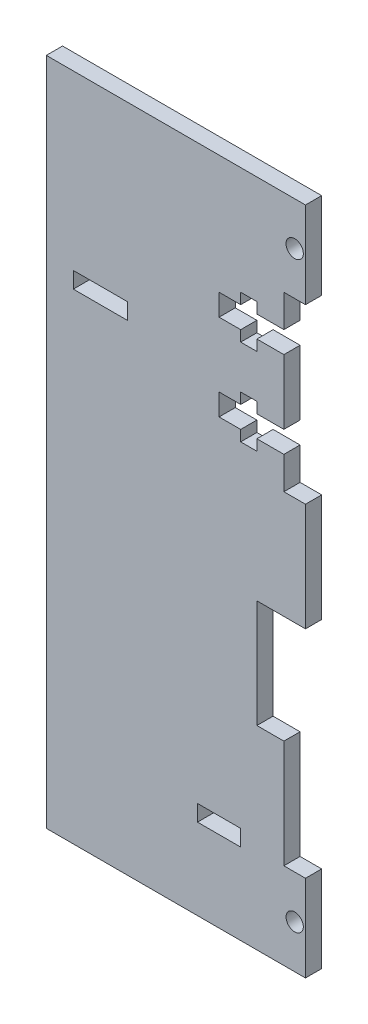
SolidWorks part; units mm, degrees
ref_plane "前视" through (0, 0, 0) normal (0, 0, 1) x (1, 0, 0)
ref_plane "上视" through (0, 0, 0) normal (0, 1, 0) x (1, 0, 0)
ref_plane "右视" through (0, 0, 0) normal (1, 0, 0) x (0, 0, -1)
sketch "草图1" plane through (0, 0, 0) normal (0, 0, 1) x (1, 0, 0)
  line L0 (0, 146) -> (0, 140)
  line L1 (4, 38) -> (4, 54)
  line L2 (-44, 38) -> (-44, 162)
  line L3 (-44, 162) -> (0, 162)
  line L4 (0, 162) -> (4, 162)
  line L5 (4, 162) -> (4, 146)
  line L6 (4, 146) -> (0, 146)
  line L7 (4, 38) -> (-44, 38)
  line L8 (4, 54) -> (0, 54)
  line L10 (0, 54) -> (0, 74)
  line L11 (4, 114) -> (4, 94)
  line L12 (-27.8711, 84) -> (21.6643, 84) construction
  line L14 (-32, 130) -> (-39, 130)
  line L16 (15.9655, 138) -> (-24.4172, 138) construction
  line L17 (-5, 94) -> (-5, 74)
  line L18 (-12, 136) -> (-12, 140)
  line L19 (-12, 140) -> (-8, 140)
  line L20 (-8, 140) -> (-8, 142)
  line L21 (-8, 142) -> (-5, 142)
  line L22 (-5, 142) -> (-5, 140)
  line L23 (-5, 140) -> (0, 140)
  line L24 (-16.0405, 114) -> (46.0459, 114) construction
  line L25 (-34.8085, 54) -> (60.6695, 54) construction
  line L30 (-5, 136) -> (0, 136)
  line L31 (-5, 134) -> (-5, 136)
  line L32 (-8, 134) -> (-5, 134)
  line L33 (-8, 136) -> (-8, 134)
  line L34 (-12, 136) -> (-8, 136)
  line L41 (0, 136) -> (0, 124)
  line L44 (-39, 130) -> (-39, 127)
  line L45 (15.9655, 122) -> (-24.4172, 122) construction
  line L46 (-39, 127) -> (-29, 127)
  line L47 (-16, 56) -> (-8, 56)
  line L48 (-16, 56) -> (-16, 53)
  line L49 (-16, 53) -> (-8, 53)
  line L50 (-12, 124) -> (-8, 124)
  line L51 (-8, 124) -> (-8, 126)
  line L52 (-8, 56) -> (-8, 53)
  line L57 (4, 94) -> (-5, 94)
  line L62 (-8, 126) -> (-5, 126)
  line L63 (-5, 126) -> (-5, 124)
  line L64 (-5, 124) -> (0, 124)
  line L65 (-5, 120) -> (0, 120)
  line L66 (-5, 118) -> (-5, 120)
  line L67 (-5, 74) -> (0, 74)
  line L69 (-29, 130) -> (-32, 130)
  line L70 (-29, 127) -> (-29, 130)
  line L71 (-8, 118) -> (-5, 118)
  line L72 (-8, 120) -> (-8, 118)
  line L73 (-12, 120) -> (-8, 120)
  line L74 (-12, 124) -> (-12, 120)
  line L75 (0, 114) -> (0, 120)
  line L76 (0, 114) -> (4, 114)
  circle A0 centre (2, 154) radius 1.6
  circle A1 centre (2, 46) radius 1.6
  point P41 (-12, 138)
  point P86 (-12, 122)
  dimension "D11" = 2
  dimension "D12" = 2
  dimension "D13" = 2
  dimension "D25" = 3.2
  dimension "D26" = 3.2
  dimension "D7" = 4
  dimension "D31" = 8
  dimension "D29" = 8
  dimension "D4" = 16
  dimension "D6" = 4
  dimension "D8" = 38
  dimension "D9" = 3
  dimension "D10" = 10
  dimension "D14" = 3
  dimension "D15" = 5
  dimension "D16" = 12
  dimension "D17" = 8
  dimension "D18" = 10
  dimension "D19" = 10
  dimension "D20" = 9
  dimension "D21" = 30
  dimension "D22" = 30
  dimension "D23" = 124
  dimension "D24" = 16
  dimension "D27" = 48
  dimension "D32" = 2
  dimension "D35" = 29
  dimension "D36" = 44
  dimension "D37" = 3
  dimension "D38" = 106
  dimension "D51" = 3
  dimension "D53" = 8
extrude "凸台-拉伸1" add sketch "草图1" along normal blind 3
